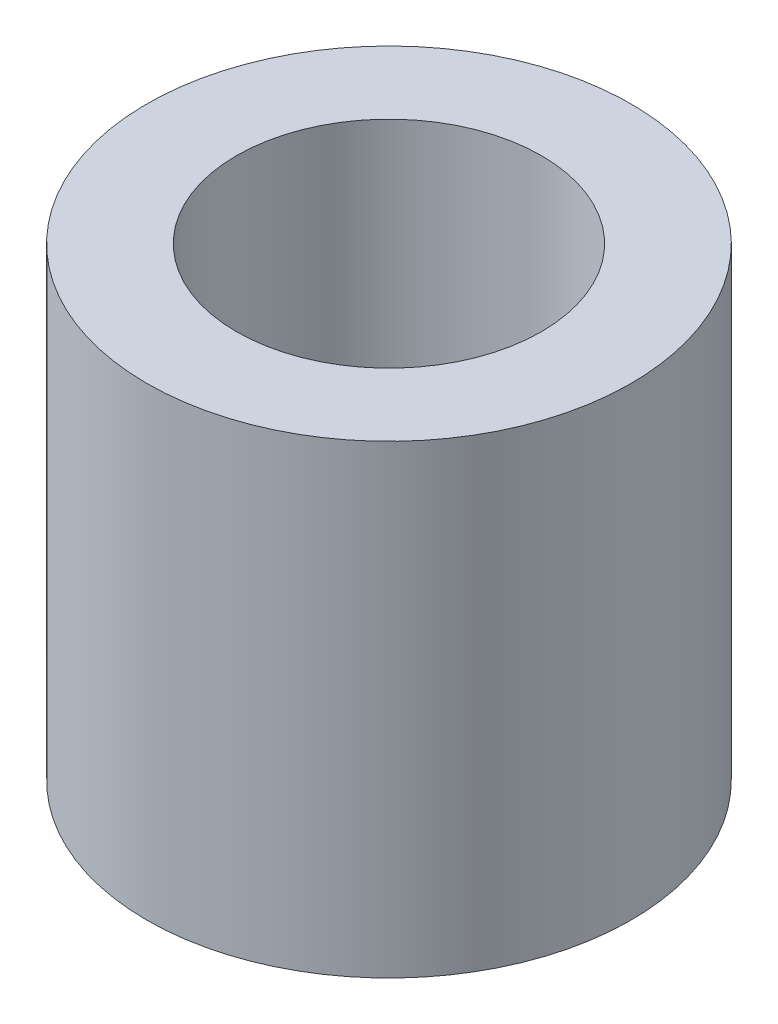
SolidWorks part; units mm, degrees
material "6061-T6 (SS)"
ref_plane "X-Y Datum" through (0, 0, 0) normal (0, 0, 1) x (1, 0, 0)
ref_plane "X-Z Datum" through (0, 0, 0) normal (0, 1, 0) x (1, 0, 0)
ref_plane "Y-Z Datum" through (0, 0, 0) normal (1, 0, 0) x (0, 0, -1)
sketch "Sketch1" plane through (0, 0, 0) normal (0, 1, 0) x (1, 0, 0)
  circle A0 centre (0, 0) radius 3.175
  circle A1 centre (0, 0) radius 2
  dimension "D1" = 6.35
  dimension "D2" = 4
extrude "Boss-Extrude1" add sketch "Sketch1" against normal blind 6.096
